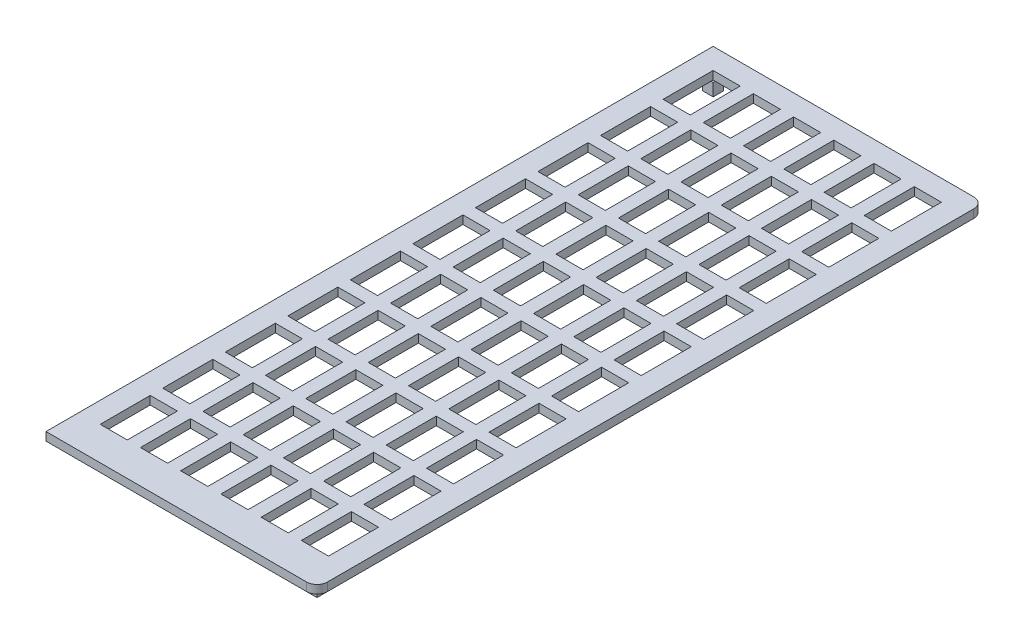
SolidWorks part; units mm, degrees
ref_plane "Front Plane" through (0, 0, 0) normal (0, 0, 1) x (1, 0, 0)
ref_plane "Top Plane" through (0, 0, 0) normal (0, 1, 0) x (1, 0, 0)
ref_plane "Right Plane" through (0, 0, 0) normal (1, 0, 0) x (0, 0, -1)
sketch "Sketch1" plane through (0, 0, 0) normal (0, 1, 0) x (1, 0, 0)
  line L0 (-298.6294, 30.6091) -> (-298.6294, 6.6091)
  line L1 (-308.6294, 40.6091) -> (-183.6294, 40.6091)
  line L2 (-308.6294, 40.6091) -> (-308.6294, -279.3909)
  line L3 (-308.6294, -279.3909) -> (-183.6294, -279.3909)
  line L4 (-178.6294, 35.6091) -> (-178.6294, -274.3909)
  line L5 (-298.6294, 6.6091) -> (-285.6294, 6.6091)
  line L6 (-285.6294, 6.6091) -> (-285.6294, 30.6091)
  line L7 (-285.6294, 30.6091) -> (-298.6294, 30.6091)
  line L8 (-266.3294, 30.6091) -> (-279.3294, 30.6091)
  line L9 (-279.3294, 30.6091) -> (-279.3294, 6.6091)
  line L10 (-279.3294, 6.6091) -> (-266.3294, 6.6091)
  line L11 (-266.3294, 6.6091) -> (-266.3294, 30.6091)
  line L12 (-247.0294, 30.6091) -> (-260.0294, 30.6091)
  line L13 (-260.0294, 30.6091) -> (-260.0294, 6.6091)
  line L14 (-260.0294, 6.6091) -> (-247.0294, 6.6091)
  line L15 (-247.0294, 6.6091) -> (-247.0294, 30.6091)
  line L16 (-227.7294, 30.6091) -> (-240.7294, 30.6091)
  line L17 (-240.7294, 30.6091) -> (-240.7294, 6.6091)
  line L18 (-240.7294, 6.6091) -> (-227.7294, 6.6091)
  line L19 (-227.7294, 6.6091) -> (-227.7294, 30.6091)
  line L20 (-208.4294, 30.6091) -> (-221.4294, 30.6091)
  line L21 (-221.4294, 30.6091) -> (-221.4294, 6.6091)
  line L22 (-221.4294, 6.6091) -> (-208.4294, 6.6091)
  line L23 (-208.4294, 6.6091) -> (-208.4294, 30.6091)
  line L24 (-189.1294, 30.6091) -> (-202.1294, 30.6091)
  line L25 (-202.1294, 30.6091) -> (-202.1294, 6.6091)
  line L26 (-202.1294, 6.6091) -> (-189.1294, 6.6091)
  line L27 (-189.1294, 6.6091) -> (-189.1294, 30.6091)
  line L28 (-266.3294, 0.6091) -> (-279.3294, 0.6091)
  line L29 (-279.3294, 0.6091) -> (-279.3294, -23.3909)
  line L30 (-279.3294, -23.3909) -> (-266.3294, -23.3909)
  line L31 (-266.3294, -23.3909) -> (-266.3294, 0.6091)
  line L32 (-247.0294, 0.6091) -> (-260.0294, 0.6091)
  line L33 (-260.0294, 0.6091) -> (-260.0294, -23.3909)
  line L34 (-260.0294, -23.3909) -> (-247.0294, -23.3909)
  line L35 (-247.0294, -23.3909) -> (-247.0294, 0.6091)
  line L36 (-227.7294, 0.6091) -> (-240.7294, 0.6091)
  line L37 (-240.7294, 0.6091) -> (-240.7294, -23.3909)
  line L38 (-240.7294, -23.3909) -> (-227.7294, -23.3909)
  line L39 (-227.7294, -23.3909) -> (-227.7294, 0.6091)
  line L40 (-208.4294, 0.6091) -> (-221.4294, 0.6091)
  line L41 (-221.4294, 0.6091) -> (-221.4294, -23.3909)
  line L42 (-221.4294, -23.3909) -> (-208.4294, -23.3909)
  line L43 (-208.4294, -23.3909) -> (-208.4294, 0.6091)
  line L44 (-189.1294, 0.6091) -> (-202.1294, 0.6091)
  line L45 (-202.1294, 0.6091) -> (-202.1294, -23.3909)
  line L46 (-202.1294, -23.3909) -> (-189.1294, -23.3909)
  line L47 (-189.1294, -23.3909) -> (-189.1294, 0.6091)
  line L48 (-266.3294, -29.3909) -> (-279.3294, -29.3909)
  line L49 (-279.3294, -29.3909) -> (-279.3294, -53.3909)
  line L50 (-279.3294, -53.3909) -> (-266.3294, -53.3909)
  line L51 (-266.3294, -53.3909) -> (-266.3294, -29.3909)
  line L52 (-247.0294, -29.3909) -> (-260.0294, -29.3909)
  line L53 (-260.0294, -29.3909) -> (-260.0294, -53.3909)
  line L54 (-260.0294, -53.3909) -> (-247.0294, -53.3909)
  line L55 (-247.0294, -53.3909) -> (-247.0294, -29.3909)
  line L56 (-227.7294, -29.3909) -> (-240.7294, -29.3909)
  line L57 (-240.7294, -29.3909) -> (-240.7294, -53.3909)
  line L58 (-240.7294, -53.3909) -> (-227.7294, -53.3909)
  line L59 (-227.7294, -53.3909) -> (-227.7294, -29.3909)
  line L60 (-208.4294, -29.3909) -> (-221.4294, -29.3909)
  line L61 (-221.4294, -29.3909) -> (-221.4294, -53.3909)
  line L62 (-221.4294, -53.3909) -> (-208.4294, -53.3909)
  line L63 (-208.4294, -53.3909) -> (-208.4294, -29.3909)
  line L64 (-189.1294, -29.3909) -> (-202.1294, -29.3909)
  line L65 (-202.1294, -29.3909) -> (-202.1294, -53.3909)
  line L66 (-202.1294, -53.3909) -> (-189.1294, -53.3909)
  line L67 (-189.1294, -53.3909) -> (-189.1294, -29.3909)
  line L68 (-266.3294, -59.3909) -> (-279.3294, -59.3909)
  line L69 (-279.3294, -59.3909) -> (-279.3294, -83.3909)
  line L70 (-279.3294, -83.3909) -> (-266.3294, -83.3909)
  line L71 (-266.3294, -83.3909) -> (-266.3294, -59.3909)
  line L72 (-247.0294, -59.3909) -> (-260.0294, -59.3909)
  line L73 (-260.0294, -59.3909) -> (-260.0294, -83.3909)
  line L74 (-260.0294, -83.3909) -> (-247.0294, -83.3909)
  line L75 (-247.0294, -83.3909) -> (-247.0294, -59.3909)
  line L76 (-227.7294, -59.3909) -> (-240.7294, -59.3909)
  line L77 (-240.7294, -59.3909) -> (-240.7294, -83.3909)
  line L78 (-240.7294, -83.3909) -> (-227.7294, -83.3909)
  line L79 (-227.7294, -83.3909) -> (-227.7294, -59.3909)
  line L80 (-208.4294, -59.3909) -> (-221.4294, -59.3909)
  line L81 (-221.4294, -59.3909) -> (-221.4294, -83.3909)
  line L82 (-221.4294, -83.3909) -> (-208.4294, -83.3909)
  line L83 (-208.4294, -83.3909) -> (-208.4294, -59.3909)
  line L84 (-189.1294, -59.3909) -> (-202.1294, -59.3909)
  line L85 (-202.1294, -59.3909) -> (-202.1294, -83.3909)
  line L86 (-202.1294, -83.3909) -> (-189.1294, -83.3909)
  line L87 (-189.1294, -83.3909) -> (-189.1294, -59.3909)
  line L88 (-266.3294, -89.3909) -> (-279.3294, -89.3909)
  line L89 (-279.3294, -89.3909) -> (-279.3294, -113.3909)
  line L90 (-279.3294, -113.3909) -> (-266.3294, -113.3909)
  line L91 (-266.3294, -113.3909) -> (-266.3294, -89.3909)
  line L92 (-247.0294, -89.3909) -> (-260.0294, -89.3909)
  line L93 (-260.0294, -89.3909) -> (-260.0294, -113.3909)
  line L94 (-260.0294, -113.3909) -> (-247.0294, -113.3909)
  line L95 (-247.0294, -113.3909) -> (-247.0294, -89.3909)
  line L96 (-227.7294, -89.3909) -> (-240.7294, -89.3909)
  line L97 (-240.7294, -89.3909) -> (-240.7294, -113.3909)
  line L98 (-240.7294, -113.3909) -> (-227.7294, -113.3909)
  line L99 (-227.7294, -113.3909) -> (-227.7294, -89.3909)
  line L100 (-208.4294, -89.3909) -> (-221.4294, -89.3909)
  line L101 (-221.4294, -89.3909) -> (-221.4294, -113.3909)
  line L102 (-221.4294, -113.3909) -> (-208.4294, -113.3909)
  line L103 (-208.4294, -113.3909) -> (-208.4294, -89.3909)
  line L104 (-189.1294, -89.3909) -> (-202.1294, -89.3909)
  line L105 (-202.1294, -89.3909) -> (-202.1294, -113.3909)
  line L106 (-202.1294, -113.3909) -> (-189.1294, -113.3909)
  line L107 (-189.1294, -113.3909) -> (-189.1294, -89.3909)
  line L108 (-266.3294, -119.3909) -> (-279.3294, -119.3909)
  line L109 (-279.3294, -119.3909) -> (-279.3294, -143.3909)
  line L110 (-279.3294, -143.3909) -> (-266.3294, -143.3909)
  line L111 (-266.3294, -143.3909) -> (-266.3294, -119.3909)
  line L112 (-247.0294, -119.3909) -> (-260.0294, -119.3909)
  line L113 (-260.0294, -119.3909) -> (-260.0294, -143.3909)
  line L114 (-260.0294, -143.3909) -> (-247.0294, -143.3909)
  line L115 (-247.0294, -143.3909) -> (-247.0294, -119.3909)
  line L116 (-227.7294, -119.3909) -> (-240.7294, -119.3909)
  line L117 (-240.7294, -119.3909) -> (-240.7294, -143.3909)
  line L118 (-240.7294, -143.3909) -> (-227.7294, -143.3909)
  line L119 (-227.7294, -143.3909) -> (-227.7294, -119.3909)
  line L120 (-208.4294, -119.3909) -> (-221.4294, -119.3909)
  line L121 (-221.4294, -119.3909) -> (-221.4294, -143.3909)
  line L122 (-221.4294, -143.3909) -> (-208.4294, -143.3909)
  line L123 (-208.4294, -143.3909) -> (-208.4294, -119.3909)
  line L124 (-189.1294, -119.3909) -> (-202.1294, -119.3909)
  line L125 (-202.1294, -119.3909) -> (-202.1294, -143.3909)
  line L126 (-202.1294, -143.3909) -> (-189.1294, -143.3909)
  line L127 (-189.1294, -143.3909) -> (-189.1294, -119.3909)
  line L128 (-266.3294, -149.3909) -> (-279.3294, -149.3909)
  line L129 (-279.3294, -149.3909) -> (-279.3294, -173.3909)
  line L130 (-279.3294, -173.3909) -> (-266.3294, -173.3909)
  line L131 (-266.3294, -173.3909) -> (-266.3294, -149.3909)
  line L132 (-247.0294, -149.3909) -> (-260.0294, -149.3909)
  line L133 (-260.0294, -149.3909) -> (-260.0294, -173.3909)
  line L134 (-260.0294, -173.3909) -> (-247.0294, -173.3909)
  line L135 (-247.0294, -173.3909) -> (-247.0294, -149.3909)
  line L136 (-227.7294, -149.3909) -> (-240.7294, -149.3909)
  line L137 (-240.7294, -149.3909) -> (-240.7294, -173.3909)
  line L138 (-240.7294, -173.3909) -> (-227.7294, -173.3909)
  line L139 (-227.7294, -173.3909) -> (-227.7294, -149.3909)
  line L140 (-208.4294, -149.3909) -> (-221.4294, -149.3909)
  line L141 (-221.4294, -149.3909) -> (-221.4294, -173.3909)
  line L142 (-221.4294, -173.3909) -> (-208.4294, -173.3909)
  line L143 (-208.4294, -173.3909) -> (-208.4294, -149.3909)
  line L144 (-189.1294, -149.3909) -> (-202.1294, -149.3909)
  line L145 (-202.1294, -149.3909) -> (-202.1294, -173.3909)
  line L146 (-202.1294, -173.3909) -> (-189.1294, -173.3909)
  line L147 (-189.1294, -173.3909) -> (-189.1294, -149.3909)
  line L148 (-266.3294, -179.3909) -> (-279.3294, -179.3909)
  line L149 (-279.3294, -179.3909) -> (-279.3294, -203.3909)
  line L150 (-279.3294, -203.3909) -> (-266.3294, -203.3909)
  line L151 (-266.3294, -203.3909) -> (-266.3294, -179.3909)
  line L152 (-247.0294, -179.3909) -> (-260.0294, -179.3909)
  line L153 (-260.0294, -179.3909) -> (-260.0294, -203.3909)
  line L154 (-260.0294, -203.3909) -> (-247.0294, -203.3909)
  line L155 (-247.0294, -203.3909) -> (-247.0294, -179.3909)
  line L156 (-227.7294, -179.3909) -> (-240.7294, -179.3909)
  line L157 (-240.7294, -179.3909) -> (-240.7294, -203.3909)
  line L158 (-240.7294, -203.3909) -> (-227.7294, -203.3909)
  line L159 (-227.7294, -203.3909) -> (-227.7294, -179.3909)
  line L160 (-208.4294, -179.3909) -> (-221.4294, -179.3909)
  line L161 (-221.4294, -179.3909) -> (-221.4294, -203.3909)
  line L162 (-221.4294, -203.3909) -> (-208.4294, -203.3909)
  line L163 (-208.4294, -203.3909) -> (-208.4294, -179.3909)
  line L164 (-189.1294, -179.3909) -> (-202.1294, -179.3909)
  line L165 (-202.1294, -179.3909) -> (-202.1294, -203.3909)
  line L166 (-202.1294, -203.3909) -> (-189.1294, -203.3909)
  line L167 (-189.1294, -203.3909) -> (-189.1294, -179.3909)
  line L168 (-266.3294, -209.3909) -> (-279.3294, -209.3909)
  line L169 (-279.3294, -209.3909) -> (-279.3294, -233.3909)
  line L170 (-279.3294, -233.3909) -> (-266.3294, -233.3909)
  line L171 (-266.3294, -233.3909) -> (-266.3294, -209.3909)
  line L172 (-247.0294, -209.3909) -> (-260.0294, -209.3909)
  line L173 (-260.0294, -209.3909) -> (-260.0294, -233.3909)
  line L174 (-260.0294, -233.3909) -> (-247.0294, -233.3909)
  line L175 (-247.0294, -233.3909) -> (-247.0294, -209.3909)
  line L176 (-227.7294, -209.3909) -> (-240.7294, -209.3909)
  line L177 (-240.7294, -209.3909) -> (-240.7294, -233.3909)
  line L178 (-240.7294, -233.3909) -> (-227.7294, -233.3909)
  line L179 (-227.7294, -233.3909) -> (-227.7294, -209.3909)
  line L180 (-208.4294, -209.3909) -> (-221.4294, -209.3909)
  line L181 (-221.4294, -209.3909) -> (-221.4294, -233.3909)
  line L182 (-221.4294, -233.3909) -> (-208.4294, -233.3909)
  line L183 (-208.4294, -233.3909) -> (-208.4294, -209.3909)
  line L184 (-189.1294, -209.3909) -> (-202.1294, -209.3909)
  line L185 (-202.1294, -209.3909) -> (-202.1294, -233.3909)
  line L186 (-202.1294, -233.3909) -> (-189.1294, -233.3909)
  line L187 (-189.1294, -233.3909) -> (-189.1294, -209.3909)
  line L188 (-266.3294, -239.3909) -> (-279.3294, -239.3909)
  line L189 (-279.3294, -239.3909) -> (-279.3294, -263.3909)
  line L190 (-279.3294, -263.3909) -> (-266.3294, -263.3909)
  line L191 (-266.3294, -263.3909) -> (-266.3294, -239.3909)
  line L192 (-247.0294, -239.3909) -> (-260.0294, -239.3909)
  line L193 (-260.0294, -239.3909) -> (-260.0294, -263.3909)
  line L194 (-260.0294, -263.3909) -> (-247.0294, -263.3909)
  line L195 (-247.0294, -263.3909) -> (-247.0294, -239.3909)
  line L196 (-227.7294, -239.3909) -> (-240.7294, -239.3909)
  line L197 (-240.7294, -239.3909) -> (-240.7294, -263.3909)
  line L198 (-240.7294, -263.3909) -> (-227.7294, -263.3909)
  line L199 (-227.7294, -263.3909) -> (-227.7294, -239.3909)
  line L200 (-208.4294, -239.3909) -> (-221.4294, -239.3909)
  line L201 (-221.4294, -239.3909) -> (-221.4294, -263.3909)
  line L202 (-221.4294, -263.3909) -> (-208.4294, -263.3909)
  line L203 (-208.4294, -263.3909) -> (-208.4294, -239.3909)
  line L204 (-189.1294, -239.3909) -> (-202.1294, -239.3909)
  line L205 (-202.1294, -239.3909) -> (-202.1294, -263.3909)
  line L206 (-202.1294, -263.3909) -> (-189.1294, -263.3909)
  line L207 (-189.1294, -263.3909) -> (-189.1294, -239.3909)
  line L208 (-285.6294, 0.6091) -> (-298.6294, 0.6091)
  line L209 (-298.6294, 0.6091) -> (-298.6294, -23.3909)
  line L210 (-298.6294, -23.3909) -> (-285.6294, -23.3909)
  line L211 (-285.6294, -23.3909) -> (-285.6294, 0.6091)
  line L212 (-285.6294, -29.3909) -> (-298.6294, -29.3909)
  line L213 (-298.6294, -29.3909) -> (-298.6294, -53.3909)
  line L214 (-298.6294, -53.3909) -> (-285.6294, -53.3909)
  line L215 (-285.6294, -53.3909) -> (-285.6294, -29.3909)
  line L216 (-285.6294, -59.3909) -> (-298.6294, -59.3909)
  line L217 (-298.6294, -59.3909) -> (-298.6294, -83.3909)
  line L218 (-298.6294, -83.3909) -> (-285.6294, -83.3909)
  line L219 (-285.6294, -83.3909) -> (-285.6294, -59.3909)
  line L220 (-285.6294, -89.3909) -> (-298.6294, -89.3909)
  line L221 (-298.6294, -89.3909) -> (-298.6294, -113.3909)
  line L222 (-298.6294, -113.3909) -> (-285.6294, -113.3909)
  line L223 (-285.6294, -113.3909) -> (-285.6294, -89.3909)
  line L224 (-285.6294, -119.3909) -> (-298.6294, -119.3909)
  line L225 (-298.6294, -119.3909) -> (-298.6294, -143.3909)
  line L226 (-298.6294, -143.3909) -> (-285.6294, -143.3909)
  line L227 (-285.6294, -143.3909) -> (-285.6294, -119.3909)
  line L228 (-285.6294, -149.3909) -> (-298.6294, -149.3909)
  line L229 (-298.6294, -149.3909) -> (-298.6294, -173.3909)
  line L230 (-298.6294, -173.3909) -> (-285.6294, -173.3909)
  line L231 (-285.6294, -173.3909) -> (-285.6294, -149.3909)
  line L232 (-285.6294, -179.3909) -> (-298.6294, -179.3909)
  line L233 (-298.6294, -179.3909) -> (-298.6294, -203.3909)
  line L234 (-298.6294, -203.3909) -> (-285.6294, -203.3909)
  line L235 (-285.6294, -203.3909) -> (-285.6294, -179.3909)
  line L236 (-285.6294, -209.3909) -> (-298.6294, -209.3909)
  line L237 (-298.6294, -209.3909) -> (-298.6294, -233.3909)
  line L238 (-298.6294, -233.3909) -> (-285.6294, -233.3909)
  line L239 (-285.6294, -233.3909) -> (-285.6294, -209.3909)
  line L240 (-285.6294, -239.3909) -> (-298.6294, -239.3909)
  line L241 (-298.6294, -239.3909) -> (-298.6294, -263.3909)
  line L242 (-298.6294, -263.3909) -> (-285.6294, -263.3909)
  line L243 (-285.6294, -263.3909) -> (-285.6294, -239.3909)
  arc A0 (-183.6294, -279.3909) -> (-178.6294, -274.3909) centre (-183.6294, -274.3909) ccw
  arc A1 (-183.6294, 40.6091) -> (-178.6294, 35.6091) centre (-183.6294, 35.6091) cw
  point P8 (-178.6294, 40.6091)
  dimension "D3" = 5
  dimension "D1" = 320
  dimension "D2" = 130
  dimension "D4" = 13
  dimension "D5" = 24
  dimension "D6" = 10
  dimension "D7" = 10
  dimension "D8" = 6
  dimension "D9" = 10
extrude "Boss-Extrude1" add sketch "Sketch1" along normal blind 4
sketch "Sketch2" plane through (0, 0, 0) normal (0, -1, 0) x (1, 0, 0)
  line L0 (-189.6294, 273.3909) -> (-189.6294, 268.3909)
  line L1 (-189.6294, 268.3909) -> (-184.6294, 268.3909)
  line L2 (-184.6294, 268.3909) -> (-184.6294, 273.3909)
  line L3 (-184.6294, 273.3909) -> (-189.6294, 273.3909)
  line L8 (-302.6294, 273.3909) -> (-302.6294, 268.3909)
  line L9 (-302.6294, 268.3909) -> (-297.6294, 268.3909)
  line L10 (-297.6294, 268.3909) -> (-297.6294, 273.3909)
  line L11 (-297.6294, 273.3909) -> (-302.6294, 273.3909)
  line L12 (-308.6294, -40.6091) -> (-308.6294, 279.3909) construction
  line L13 (-308.6294, 279.3909) -> (-183.6294, 279.3909) construction
  line L14 (-178.6294, 274.3909) -> (-178.6294, -35.6091) construction
  line L16 (-302.6294, -29.6091) -> (-302.6294, -34.6091)
  line L17 (-302.6294, -34.6091) -> (-297.6294, -34.6091)
  line L18 (-297.6294, -34.6091) -> (-297.6294, -29.6091)
  line L19 (-297.6294, -29.6091) -> (-302.6294, -29.6091)
  line L20 (-183.6294, -40.6091) -> (-308.6294, -40.6091) construction
  dimension "D1" = 5
  dimension "D2" = 5
  dimension "D3" = 5
  dimension "D4" = 5
  dimension "D5" = 5
  dimension "D6" = 5
  dimension "D7" = 6
  dimension "D8" = 6
  dimension "D9" = 6
  dimension "D10" = 6
  dimension "D11" = 6
  dimension "D12" = 6
extrude "Boss-Extrude2" add sketch "Sketch2" along normal blind 6
